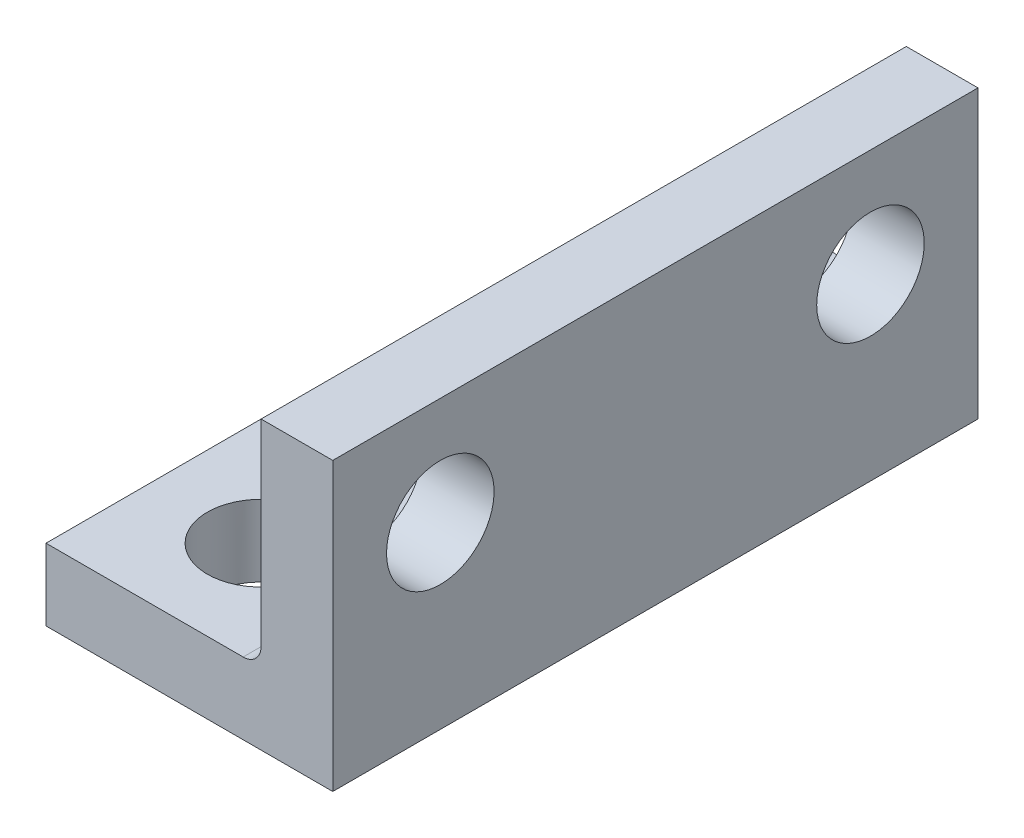
SolidWorks part; units mm, degrees
ref_plane "Front Plane" through (0, 0, 0) normal (0, 0, 1) x (1, 0, 0)
ref_plane "Top Plane" through (0, 0, 0) normal (0, 1, 0) x (1, 0, 0)
ref_plane "Right Plane" through (0, 0, 0) normal (1, 0, 0) x (0, 0, -1)
sketch "Sketch1" plane through (0, 0, 0) normal (0, 0, 1) x (1, 0, 0)
  line L0 (0, 0) -> (-8, 0)
  line L1 (-8, 0) -> (-8, 2)
  line L2 (-8, 2) -> (-2, 2)
  line L3 (0, 0) -> (0, 8)
  line L4 (0, 8) -> (-2, 8)
  line L5 (-2, 8) -> (-2, 2)
  dimension "D1" = 2
  dimension "D2" = 2
  dimension "D3" = 8
  dimension "D4" = 8
extrude "Boss-Extrude1" add sketch "Sketch1" along normal blind 18
sketch "Sketch2" plane through (0, 0, 0) normal (1, 0, 0) x (0, 0, -1)
  line L0 (-9, 8) -> (-9, 0) construction
  line L1 (-18, 8) -> (0, 8) construction
  line L2 (-18, 0) -> (0, 0) construction
  line L3 (-15, 5) -> (-3, 5) construction
  circle A0 centre (-15, 5) radius 1.5
  circle A1 centre (-3, 5) radius 1.5
  point P9 (-9, 5)
  dimension "D3" = 3
  dimension "D4" = 3
  dimension "D1" = 12
  dimension "D2" = 3
extrude "Cut-Extrude1" cut sketch "Sketch2" against normal through all both and the other way through all
sketch "Sketch3" plane through (0, 0, 0) normal (0, -1, 0) x (1, 0, 0)
  line L0 (-8, 9) -> (0, 9) construction
  line L1 (-8, 18) -> (-8, 0) construction
  line L2 (0, 18) -> (0, 0) construction
  line L3 (-5, 15) -> (-5, 3) construction
  circle A0 centre (-5, 15) radius 1.5
  circle A1 centre (-5, 3) radius 1.5
  point P9 (-5, 9)
  point P10 (0, 0)
  dimension "D3" = 3
  dimension "D4" = 3
  dimension "D1" = 12
  dimension "D2" = 3
extrude "Cut-Extrude2" cut sketch "Sketch3" against normal through all both and the other way through all
fillet "Fillet1" radius 0.5 1 edges at (-2, 2, 9)
